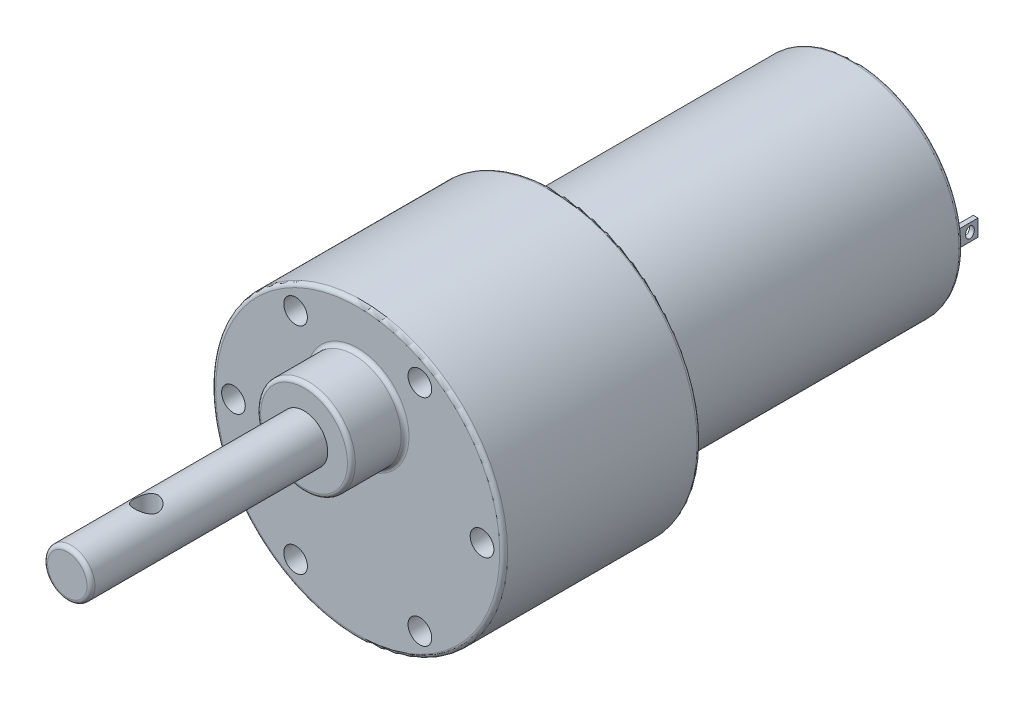
SolidWorks part; units mm, degrees
ref_plane "Front Plane" through (0, 0, 0) normal (0, 0, 1) x (1, 0, 0)
ref_plane "Top Plane" through (0, 0, 0) normal (0, 1, 0) x (1, 0, 0)
ref_plane "Right Plane" through (0, 0, 0) normal (1, 0, 0) x (0, 0, -1)
sketch "Sketch1" plane through (0, 0, 0) normal (0, 0, 1) x (1, 0, 0)
  circle A0 centre (0, 0) radius 18.5
  dimension "D1" = 37
extrude "Boss-Extrude1" add sketch "Sketch1" along normal blind 25
sketch "Sketch2" plane through (0, 0, 25) normal (0, 0, 1) x (1, 0, 0)
  circle A0 centre (0, 7) radius 6
  dimension "D1" = 12
  dimension "D2" = 7
extrude "Boss-Extrude2" add sketch "Sketch2" along normal blind 6.8
sketch "Sketch3" plane through (0, 0, 31.8) normal (0, 0, 1) x (1, 0, 0)
  circle A0 centre (0, 7) radius 3
  dimension "D1" = 6
extrude "Boss-Extrude3" add sketch "Sketch3" along normal blind 30
sketch "Sketch4" plane through (0, 0, 0) normal (0, 0, -1) x (-1, 0, 0)
  circle A0 centre (0, 0) radius 13.7
  dimension "D1" = 27.4
extrude "Boss-Extrude4" add sketch "Sketch4" along normal blind 38
sketch "Sketch5" plane through (0, 0, -38) normal (0, 0, -1) x (-1, 0, 0)
  circle A0 centre (0, 0) radius 5
  dimension "D1" = 10
extrude "Boss-Extrude5" add sketch "Sketch5" along normal blind 2
sketch "Sketch6" plane through (0, 0, -40) normal (0, 0, -1) x (-1, 0, 0)
  circle A0 centre (0, 0) radius 1.5
  dimension "D1" = 3
extrude "Boss-Extrude6" add sketch "Sketch6" along normal blind 1
sketch "Sketch7" plane through (0, 0, -38) normal (0, 0, -1) x (-1, 0, 0)
  line L1 (-12.6, -1.0565) -> (-12, -1.0565)
  line L2 (-12.6, -1.0565) -> (-12.6, 1.0565)
  line L3 (-12.6, 1.0565) -> (-12, 1.0565)
  line L4 (-12, -1.0565) -> (-12, 1.0565)
  line L5 (-12.6, -1.0565) -> (-12, 1.0565) construction
  line L6 (-12.6, 1.0565) -> (-12, -1.0565) construction
  line L7 (12, -1.0565) -> (12.6, -1.0565)
  line L8 (12, -1.0565) -> (12, 1.0565)
  line L9 (12, 1.0565) -> (12.6, 1.0565)
  line L10 (12.6, -1.0565) -> (12.6, 1.0565)
  line L11 (12, -1.0565) -> (12.6, 1.0565) construction
  line L12 (12, 1.0565) -> (12.6, -1.0565) construction
  point P0 (-12.3, 0)
  point P5 (12.3, 0)
  dimension "D1" = 0.6
  dimension "D2" = 0.6
  dimension "D3" = 12.3
  dimension "D4" = 12.3
extrude "Boss-Extrude7" add sketch "Sketch7" along normal blind 3
sketch "Sketch9" plane through (12.6, 0, 0) normal (1, 0, 0) x (0, 0, -1)
  ellipse E0 centre (39.9795, 0) end of major axis (39.9795, 0.7031) minor radius 0.549
extrude "Cut-Extrude1" cut sketch "Sketch9" against normal blind 3
sketch "Sketch10" plane through (-12.6, 0, 0) normal (-1, 0, 0) x (0, 0, 1)
  ellipse E0 centre (-39.9166, 0) end of major axis (-39.9166, 0.7154) minor radius 0.4822
extrude "Cut-Extrude2" cut sketch "Sketch10" against normal blind 3
sketch "Sketch11" plane through (0, 0, 0) normal (0, 1, 0) x (1, 0, 0)
  line L0 (-3, -61.8) -> (3, -61.8) construction
  circle A0 centre (0, -51.8) radius 1.5
  dimension "D1" = 3
  dimension "D2" = 10
extrude "Cut-Extrude3" cut sketch "Sketch11" along normal through all
sketch "Sketch12" plane through (0, 0, 25) normal (0, 0, 1) x (1, 0, 0)
  circle A0 centre (-15.7499, 0) radius 1.5
  circle A1 centre (-7.8749, 13.6399) radius 1.5
  circle A2 centre (7.8751, 13.6399) radius 1.5
  circle A3 centre (15.7501, 0) radius 1.5
  circle A4 centre (7.8751, -13.6399) radius 1.5
  circle A5 centre (-7.8749, -13.6399) radius 1.5
  point P15 (0.0001, 0)
  dimension "D1" = 3
  dimension "D3" = 31.5
  dimension "D2" = 6
extrude "Cut-Extrude4" cut sketch "Sketch12" against normal blind 3
fillet "Fillet1" radius 0.5 1 edges at (18.5, 0, 25)
fillet "Fillet2" radius 0.5 1 edges at (6, 7, 25)
fillet "Fillet3" radius 0.5 1 edges at (6, 7, 31.8)
fillet "Fillet4" radius 0.5 1 edges at (3, 7, 61.8)
fillet "Fillet5" radius 0.5 5 edges at (-1.5, 0, -41) (-5, 0, -38) (-5, 0, -40) (-13.7, 0, -38) (18.5, 0, 0)
